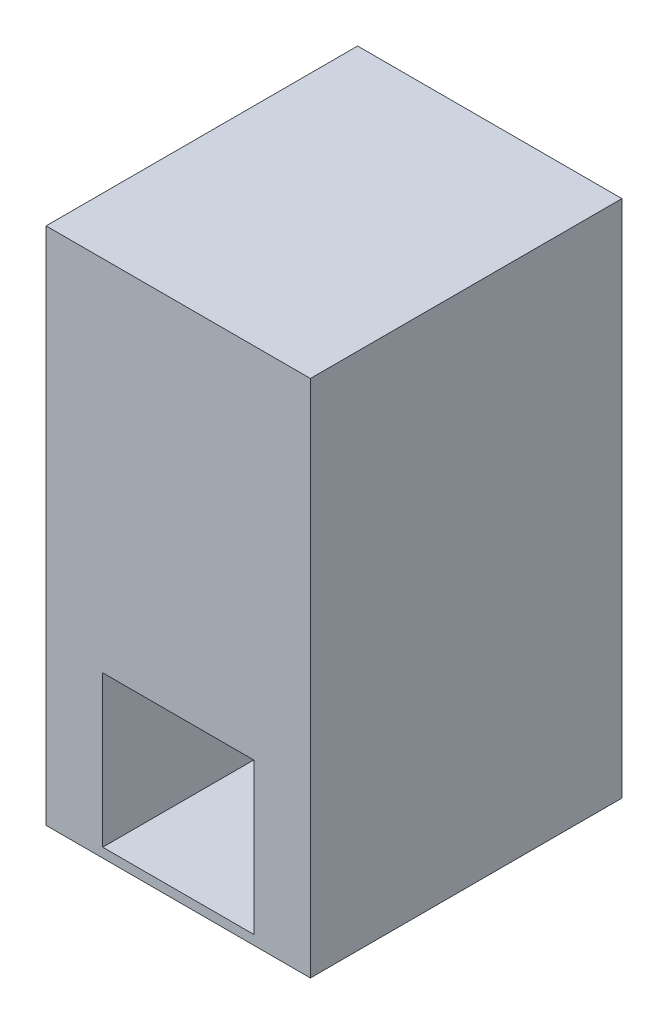
SolidWorks part; units mm, degrees
ref_plane "Front Plane" through (0, 0, 0) normal (0, 0, 1) x (1, 0, 0)
ref_plane "Top Plane" through (0, 0, 0) normal (0, 1, 0) x (1, 0, 0)
ref_plane "Right Plane" through (0, 0, 0) normal (1, 0, 0) x (0, 0, -1)
sketch "Sketch2" plane through (0, 0, 0) normal (0, 1, 0) x (1, 0, 0)
  line L0 (-355.6, 419.1) -> (355.6, -419.1) construction
  line L1 (-355.6, -419.1) -> (355.6, -419.1)
  line L2 (-355.6, -419.1) -> (-355.6, 419.1)
  line L3 (-355.6, 419.1) -> (355.6, 419.1)
  line L4 (355.6, -419.1) -> (355.6, 419.1)
  dimension "D1" = 838.2
  dimension "D2" = 711.2
extrude "Boss-Extrude1" add sketch "Sketch2" along normal blind 1397
sketch "Sketch6" plane through (0, 0, 419.1) normal (0, 0, 1) x (1, 0, 0)
  line L0 (-355.6, 1397) -> (-355.6, 0) construction
  line L1 (203.2, 25.4) -> (-203.2, 25.4)
  line L2 (203.2, 25.4) -> (203.2, 431.8)
  line L3 (203.2, 431.8) -> (-203.2, 431.8)
  line L4 (-203.2, 25.4) -> (-203.2, 431.8)
  line L7 (-355.6, 0) -> (355.6, 0) construction
  dimension "D1" = 152.4
  dimension "D2" = 406.4
  dimension "D3" = 25.4
  dimension "D4" = 406.4
extrude "Cut-Extrude1" cut sketch "Sketch6" against normal blind 609.6
